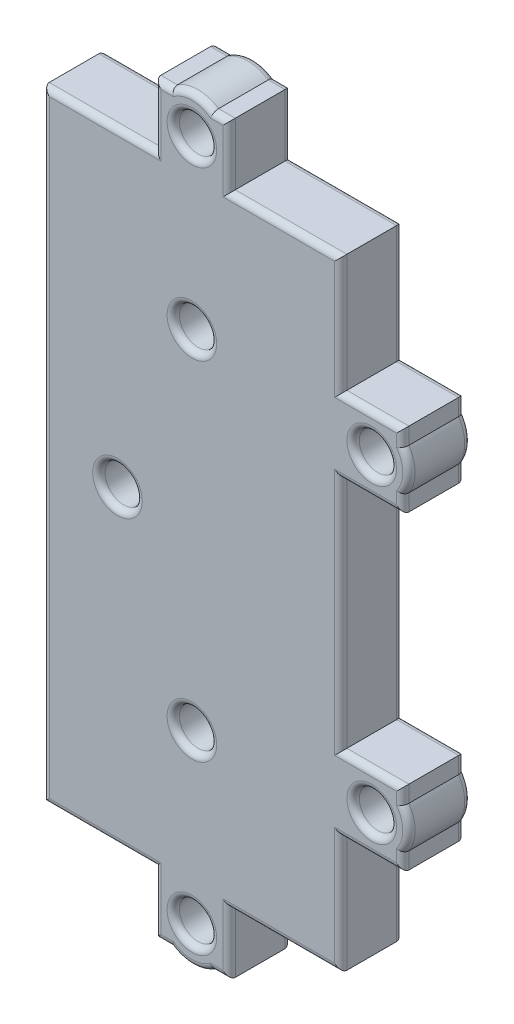
SolidWorks part; units mm, degrees
ref_plane "Plan de face" through (0, 0, 0) normal (0, 0, 1) x (1, 0, 0)
ref_plane "Plan de dessus" through (0, 0, 0) normal (0, 1, 0) x (1, 0, 0)
ref_plane "Plan de droite" through (0, 0, 0) normal (1, 0, 0) x (0, 0, -1)
sketch "Esquisse1" plane through (0, 0, 0) normal (0, 0, 1) x (1, 0, 0)
  line L0 (-35.0405, 0) -> (54.5819, 0) construction
  line L1 (-12, 25) -> (12, 25)
  line L2 (-12, 25) -> (-12, -25)
  line L3 (-12, -25) -> (12, -25)
  line L4 (12, 25) -> (12, -25)
  line L5 (-12, 25) -> (12, -25) construction
  line L6 (-12, -25) -> (12, 25) construction
  line L7 (0, 39.6923) -> (0, -46.9091) construction
  line L8 (17, 10.8417) -> (17, 9.5)
  line L9 (17, 15.5) -> (12, 15.5)
  line L10 (17, 15.5) -> (17, 14.1583)
  line L11 (17, 9.5) -> (12, 9.5)
  line L12 (12, 15.5) -> (12, 9.5)
  line L13 (17, 15.5) -> (12, 9.5) construction
  line L14 (17, 9.5) -> (12, 15.5) construction
  line L15 (17, -15.5) -> (17, -14.1583)
  line L16 (17, -10.8417) -> (17, -9.5)
  line L17 (17, -9.5) -> (12, -9.5)
  line L18 (12, -15.5) -> (12, -9.5)
  line L19 (17, -15.5) -> (12, -15.5)
  line L20 (1.6583, 30) -> (3, 30)
  line L21 (-3, 30) -> (-1.6583, 30)
  line L22 (-3, 30) -> (-3, 25)
  line L23 (-3, 25) -> (3, 25)
  line L24 (3, 30) -> (3, 25)
  line L25 (-3, 30) -> (3, 25) construction
  line L26 (-3, 25) -> (3, 30) construction
  line L27 (-3, -30) -> (-1.6583, -30)
  line L28 (-3, -30) -> (-3, -25)
  line L29 (-3, -25) -> (3, -25)
  line L30 (3, -30) -> (3, -25)
  line L31 (1.6583, -30) -> (3, -30)
  circle A0 centre (14.5, 12.5) radius 1.5
  arc A1 (17, 10.8417) -> (17, 14.1583) centre (14.5, 12.5) ccw
  circle A2 centre (14.5, -12.5) radius 1.5
  arc A3 (17, -10.8417) -> (17, -14.1583) centre (14.5, -12.5) cw
  circle A4 centre (0, 27.5) radius 1.5
  arc A6 (1.6583, 30) -> (-1.6583, 30) centre (0, 27.5) ccw
  circle A7 centre (0, -27.5) radius 1.5
  arc A8 (1.6583, -30) -> (-1.6583, -30) centre (0, -27.5) cw
  point P0 (0, 0)
  point P10 (14.5, 12.5)
  point P27 (0, 27.5)
  dimension "D6" = 3
  dimension "D7" = 6
  dimension "D10" = 3
  dimension "D1" = 50
  dimension "D2" = 24
  dimension "D3" = 12.5
  dimension "D4" = 6
  dimension "D5" = 5
  dimension "D8" = 5
  dimension "D9" = 6
extrude "Boss.-Extru.1" add sketch "Esquisse1" along normal blind 5 contours L4 L1 L2 L3 | A7 | A3 L16 L17 L4 L19 L15 A2 | L20 A6 L21 L22 L1 L24 A4 | L8 A1 L10 L9 L4 L11 A0 | L30 L29 L28 L27 A8 L31
sketch "Esquisse2" plane through (0, 0, 5) normal (0, 0, 1) x (1, 0, 0)
  circle A0 centre (0, 14) radius 1.5
  circle A1 centre (-6, 0) radius 1.5
  circle A2 centre (0, -14) radius 1.5
extrude "Enlèv. mat.-Extru.1" cut sketch "Esquisse2" against normal blind 5
fillet "Congé1" radius 0.5 70 edges at (1.5, -27.5, 5) (1.5, -27.5, 0) (16, 12.5, 5) (16, 12.5, 0) (16, -12.5, 5) (16, -12.5, 0) (1.5, 27.5, 5) (1.5, 27.5, 0) (-7.5, 25, 0) (-7.5, 25, 5) (3, 27.5, 0) (3, 27.5, 5) (2.3292, 30, 0) (2.3292, 30, 5) (0, 30.5, 0) (0, 30.5, 5) (-2.3292, 30, 0) (-2.3292, 30, 5) (-3, 27.5, 0) (-3, 27.5, 5) (7.5, 25, 0) (7.5, 25, 5) (-12, 0, 0) (-12, 0, 5) (-7.5, -25, 5) (-7.5, -25, 0) (-3, -27.5, 0) (-3, -27.5, 5) (-2.3292, -30, 0) (-2.3292, -30, 5) (0, -30.5, 0) (0, -30.5, 5) (2.3292, -30, 0) (2.3292, -30, 5) (3, -27.5, 0) (3, -27.5, 5) (7.5, -25, 5) (7.5, -25, 0) (12, 0, 0) (12, 0, 5) (14.5, -15.5, 0) (14.5, -15.5, 5) (17, -14.8292, 0) (17, -14.8292, 5) (17.5, -12.5, 0) (17.5, -12.5, 5) (17, -10.1708, 0) (17, -10.1708, 5) (14.5, -9.5, 0) (14.5, -9.5, 5) (12, 20.25, 5) (12, -20.25, 5) (12, 20.25, 0) (12, -20.25, 0) (14.5, 9.5, 0) (14.5, 9.5, 5) (17, 10.1708, 0) (17, 10.1708, 5) (17.5, 12.5, 0) (17.5, 12.5, 5) (17, 14.8292, 0) (17, 14.8292, 5) (14.5, 15.5, 0) (14.5, 15.5, 5) (1.5, -14, 0) (1.5, -14, 5) (-4.5, 0, 0) (-4.5, 0, 5) (1.5, 14, 0) (1.5, 14, 5)
